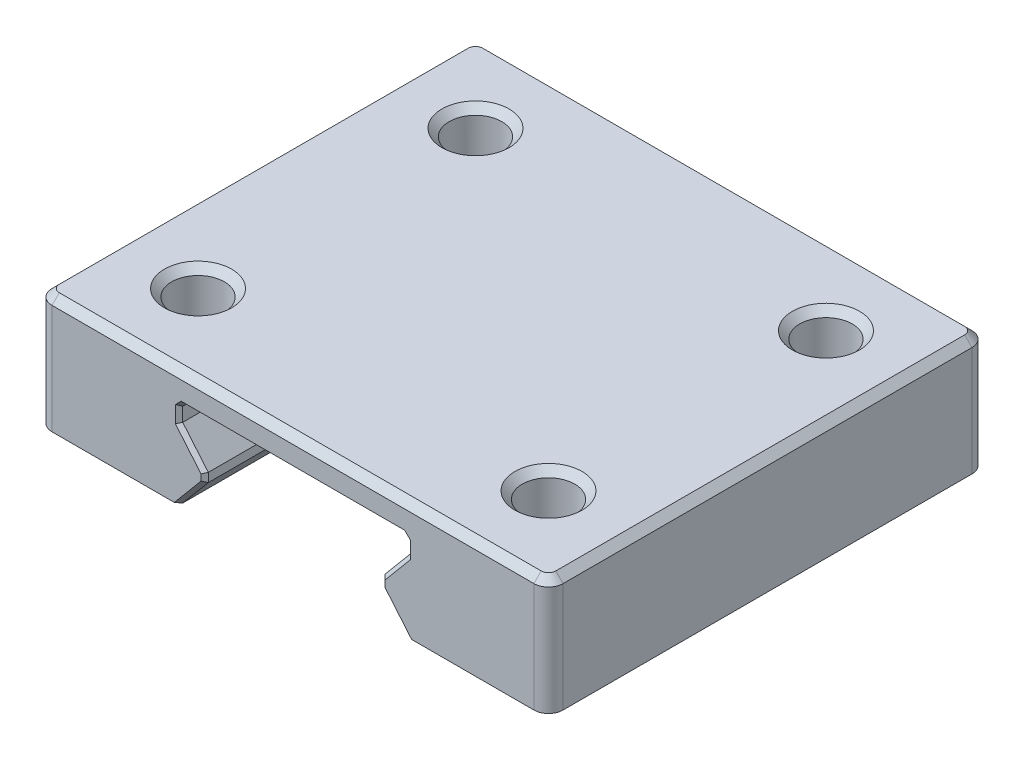
SolidWorks part; units mm, degrees
material "PET"
ref_plane "Přední rovina" through (0, 0, 0) normal (0, 0, 1) x (1, 0, 0)
ref_plane "Horní rovina" through (0, 0, 0) normal (0, 1, 0) x (1, 0, 0)
ref_plane "Pravá rovina" through (0, 0, 0) normal (1, 0, 0) x (0, 0, -1)
sketch "Skica1" plane through (0, 0, 0) normal (0, 0, 1) x (1, 0, 0)
  line L0 (17.5, 8) -> (17.5, 0) construction
  line L1 (0, 0) -> (9.7, 0)
  line L2 (0, 0) -> (0, 8)
  line L3 (0, 8) -> (35, 8)
  line L4 (35, 0) -> (35, 8)
  line L5 (0, 0) -> (35, 8) construction
  line L6 (0, 8) -> (35, 0) construction
  line L7 (9.7, 0) -> (11.4537, 2.09)
  line L8 (11.4537, 2.09) -> (11.4537, 2.7)
  line L9 (11.4537, 2.7) -> (9.7, 4.79)
  line L10 (9.7, 4.79) -> (9.7, 5.74)
  line L11 (9.95, 5.99) -> (25.05, 5.99)
  line L12 (9.7, 5.74) -> (9.95, 5.99)
  line L13 (25.3, 5.74) -> (25.05, 5.99)
  line L14 (25.3, 4.79) -> (25.3, 5.74)
  line L15 (23.5463, 2.7) -> (25.3, 4.79)
  line L16 (23.5463, 2.09) -> (23.5463, 2.7)
  line L17 (25.3, 0) -> (23.5463, 2.09)
  line L18 (25.3, 0) -> (35, 0)
  point P4 (17.5, 4)
  point P13 (9.7, 5.99)
  point P18 (17.5, 5.99)
  dimension "D1" = 35
  dimension "D2" = 8
  dimension "D3" = 15.6
  dimension "D4" = 130
  dimension "D5" = 15.6
  dimension "D6" = 2.09
  dimension "D7" = 3.29
  dimension "D8" = 50
  dimension "D9" = 0.61
extrude "Přidat vysunutím1" add sketch "Skica1" along normal blind 30
sketch "Skica2" plane through (0, 8, 0) normal (0, 1, 0) x (1, 0, 0)
  line L0 (0, -30) -> (0, 0) construction
  line L1 (5.5, -5.5) -> (29.5, -5.5) construction
  line L2 (5.5, -5.5) -> (5.5, -24.5) construction
  line L3 (5.5, -24.5) -> (29.5, -24.5) construction
  line L4 (29.5, -5.5) -> (29.5, -24.5) construction
  line L5 (5.5, -5.5) -> (29.5, -24.5) construction
  line L6 (5.5, -24.5) -> (29.5, -5.5) construction
  line L8 (35, 0) -> (0, 0) construction
  line L10 (35, -30) -> (35, 0) construction
  line L11 (35, -30) -> (0, -30) construction
  circle A0 centre (5.5, -5.5) radius 1.8
  circle A1 centre (29.5, -5.5) radius 1.8
  circle A2 centre (5.5, -24.5) radius 1.8
  circle A3 centre (29.5, -24.5) radius 1.8
  point P4 (17.5, -15)
  dimension "D1" = 3.6
  dimension "D2" = 3.6
  dimension "D3" = 3.6
  dimension "D4" = 3.6
  dimension "D5" = 5.5
  dimension "D6" = 5.5
  dimension "D7" = 5.5
  dimension "D8" = 5.5
extrude "Odebrat vysunutím1" cut sketch "Skica2" against normal up to surface (8 mm away) up to face at (30.15, 0, 15)
fillet "Zaoblit1" radius 1 4 edges at (0, 4, 30) (0, 4, 0) (35, 4, 30) (35, 4, 0)
chamfer "Zkosení2" distance 0.25 angle 45 22 edges at (24.4231, 1.045, 30) (23.5463, 2.395, 30) (24.4231, 3.745, 30) (25.3, 5.265, 30) (25.175, 5.865, 30) (17.5, 5.99, 30) (9.825, 5.865, 30) (9.7, 5.265, 30) (10.5769, 3.745, 30) (11.4537, 2.395, 30) (10.5769, 1.045, 30) (10.5769, 1.045, 0) (11.4537, 2.395, 0) (10.5769, 3.745, 0) (9.7, 5.265, 0) (9.825, 5.865, 0) (17.5, 5.99, 0) (25.175, 5.865, 0) (25.3, 5.265, 0) (24.4231, 3.745, 0) (23.5463, 2.395, 0) (24.4231, 1.045, 0)
chamfer "Zkosení3" distance 0.5 angle 45 8 edges at (17.5, 8, 0) (34.7071, 8, 0.2929) (0.2929, 8, 0.2929) (35, 8, 15) (0, 8, 15) (34.7071, 8, 29.7071) (0.2929, 8, 29.7071) (17.5, 8, 30)
chamfer "Zkosení4" distance 0.5 angle 45 4 edges at (27.7, 8, 24.5) (3.7, 8, 24.5) (27.7, 8, 5.5) (3.7, 8, 5.5)
